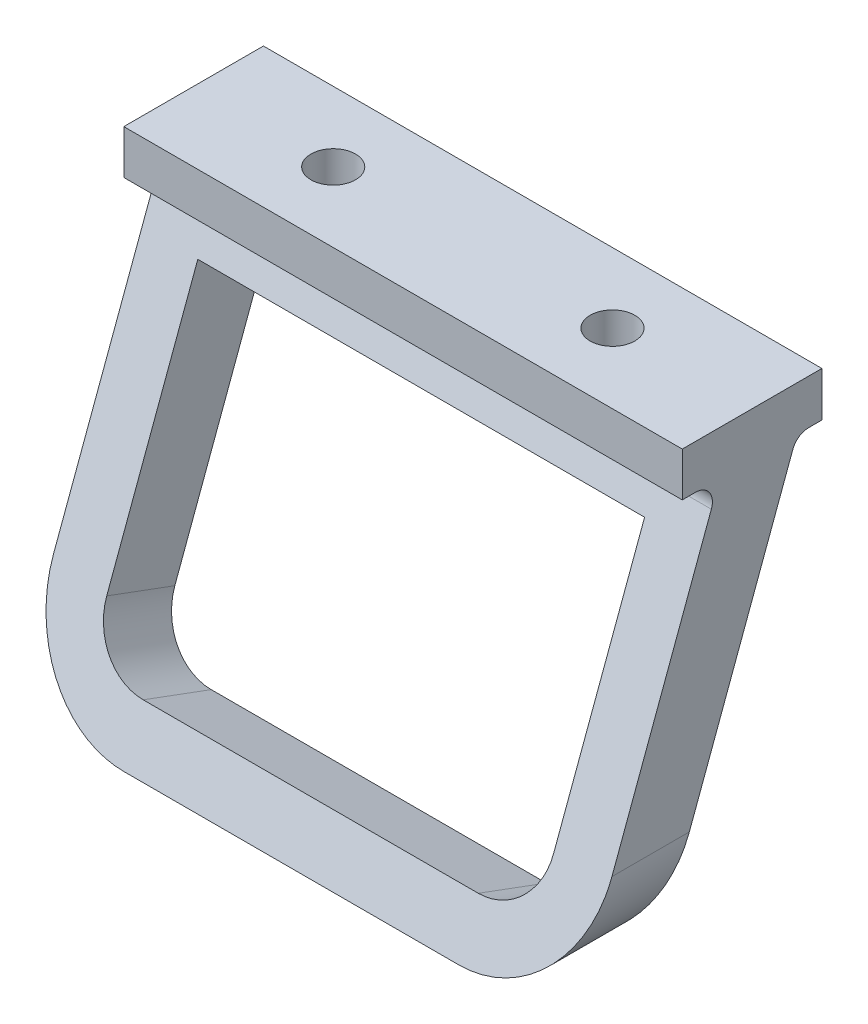
SolidWorks part; units mm, degrees
ref_plane "Front Plane" through (0, 0, 0) normal (0, 0, 1) x (1, 0, 0)
ref_plane "Top Plane" through (0, 0, 0) normal (0, 1, 0) x (1, 0, 0)
ref_plane "Right Plane" through (0, 0, 0) normal (1, 0, 0) x (0, 0, -1)
sketch "Sketch3" plane through (0, 0, 0) normal (1, 0, 0) x (0, 0, -1)
  line L8 (0, 0) -> (25.2037, 68.0696)
  line L14 (39.7963, 70.0417) -> (13.8625, 0)
  line L15 (13.8625, 0) -> (0, 0)
  line L17 (22.3903, 72.1113) -> (20, 72.1113)
  line L18 (20, 72.1113) -> (20, 80)
  line L19 (20, 80) -> (45, 80)
  line L20 (45, 80) -> (45, 72)
  line L21 (45, 72) -> (42.6097, 72)
  line L22 (24.0671, 65) -> (37.9296, 65)
  arc A0 (39.7963, 70.0417) -> (42.6097, 72) centre (42.6097, 69) cw
  arc A1 (25.2037, 68.0696) -> (22.3903, 72.1113) centre (22.3903, 69.1113) ccw
  point P12 (40.5214, 72)
  point P16 (26.7001, 72.1113)
  dimension "D7" = 3
  dimension "D1" = 80
  dimension "D2" = 13
  dimension "D3" = 8
  dimension "D4" = 25
  dimension "D6" = 45
extrude "Boss-Extrude1" add sketch "Sketch3" along normal blind 100 contours L22 L8 L15 L14 | A1 L8 L22 L14 A0 L21 L20 L19 L18 L17
fillet "Fillet1" radius 20 1 edges at (100, 0, -6.9313)
fillet "Fillet2" radius 20 1 edges at (0, 0, -6.9313)
sketch "Sketch4" plane through (0, 0, 0) normal (0, 0.3472, 0.9378) x (1, 0, 0)
  line L0 (10, 66.967) -> (10, 20)
  line L1 (20, 10) -> (80, 10)
  line L2 (90, 20) -> (90, 66.967)
  line L3 (90, 66.967) -> (10, 66.967)
  line L4 (100, 81.967) -> (0, 81.967) construction
  line L7 (0, 21.3269) -> (0, 72.5858) construction
  line L8 (80, 0) -> (20, 0) construction
  arc A0 (80, 10) -> (90, 20) centre (80, 20) ccw
  arc A1 (20, 10) -> (10, 20) centre (20, 20) cw
  dimension "D5" = 10
  dimension "D1" = 15
  dimension "D2" = 80
  dimension "D3" = 10
  dimension "D4" = 10
extrude "Cut-Extrude1" cut sketch "Sketch4" along direction (0, -0.3472, -0.9378) on the side against the normal up to next (13 mm away)
hole_wizard "Ø1.0mm Dowel Hole1" positions "Sketch5" profile "Sketch7" hole size "Ø1.0" standard "ISO"
sketch "Sketch5" plane through (0, 80, 0) normal (0, 1, 0) x (1, 0, 0)
  line L0 (0, 20) -> (0, 45) construction
  line L1 (25, 32.5) -> (75, 32.5) construction
  line L3 (100, 45) -> (0, 45) construction
  point P0 (25, 32.5)
  point P2 (75, 32.5)
  dimension "D1" = 25
  dimension "D2" = 50
  dimension "D3" = 12.5
sketch "Sketch7" plane through (25, 80, -32.5) normal (1, 0, 0) x (0, 0, 1)
  line L0 (0, 0) -> (0, 15)
  line L1 (0, 15) -> (4, 12.5966)
  line L2 (4, 12.5966) -> (4, 0)
  line L5 (4, 0) -> (0, 0)
  line L10 (0, 15) -> (-4, 12.5966) construction
  line L11 (0, -6.35) -> (0, 107.95) construction
  dimension "Hole Dia." = 8
  dimension "Hole Depth" = 15
  dimension "Drill Angle" = 118
